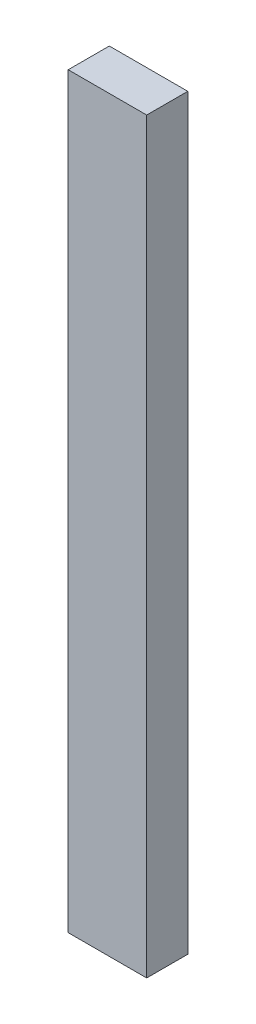
SolidWorks part; units mm, degrees
ref_plane "Front Plane" through (0, 0, 0) normal (0, 0, 1) x (1, 0, 0)
ref_plane "Top Plane" through (0, 0, 0) normal (0, 1, 0) x (1, 0, 0)
ref_plane "Right Plane" through (0, 0, 0) normal (1, 0, 0) x (0, 0, -1)
sketch "Sketch1" plane through (0, 0, 0) normal (0, 1, 0) x (1, 0, 0)
  line L1 (-60, 30) -> (60, 30)
  line L2 (-60, 30) -> (-60, -30)
  line L3 (-60, -30) -> (60, -30)
  line L4 (60, 30) -> (60, -30)
  line L5 (-60, 30) -> (60, -30) construction
  line L6 (-60, -30) -> (60, 30) construction
  point P0 (0, 0)
  dimension "D1" = 120
  dimension "D2" = 60
extrude "Extrude-Thin1" add sketch "Sketch1" along normal mid plane 1200 thin thin type one direction wall 3
ref_plane "Plane1" through (0, 600, 0) normal (0, 1, 0) x (1, 0, 0)
sketch "Sketch2" plane through (0, 600, 0) normal (0, 1, 0) x (1, 0, 0)
  line L0 (-60, -30) -> (-60, 30)
  line L1 (-60, 30) -> (60, 30)
  line L2 (60, 30) -> (60, -30)
  line L3 (60, -30) -> (-60, -30)
extrude "Boss-Extrude1" add sketch "Sketch2" against normal blind 3
